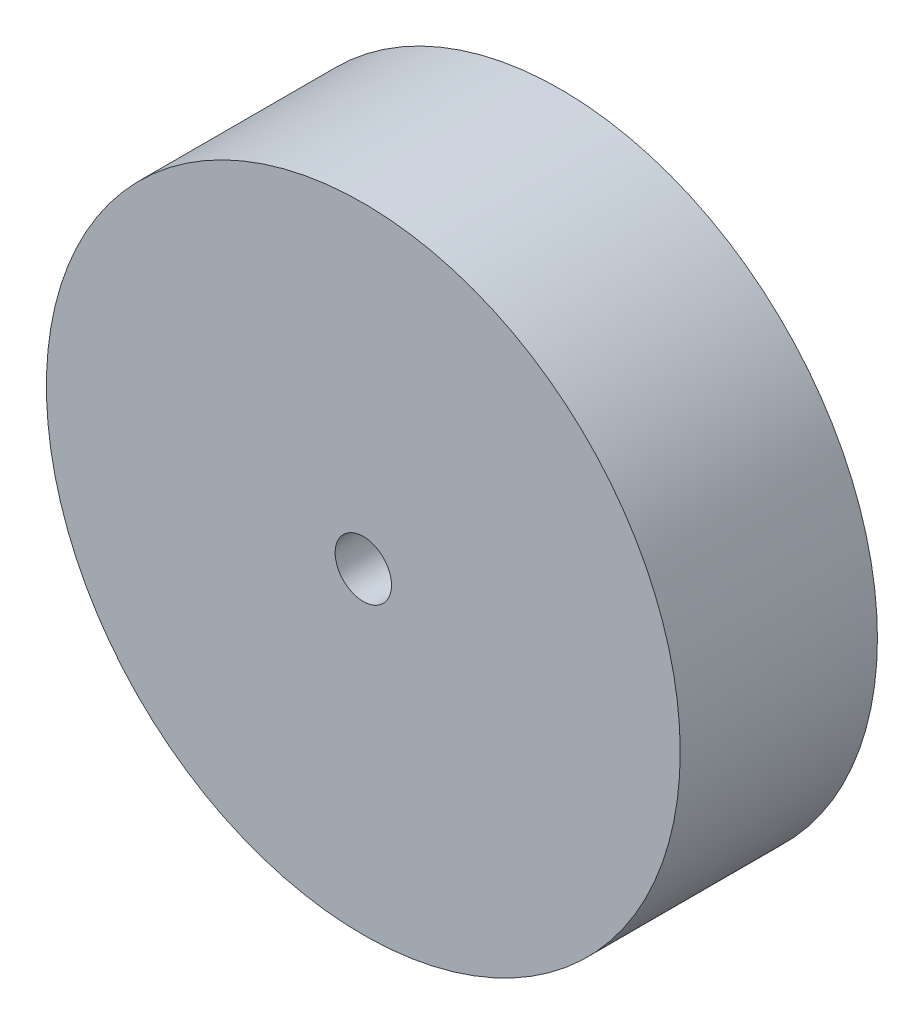
SolidWorks part; units mm, degrees
material "Beech"
ref_plane "Front Plane" through (0, 0, 0) normal (0, 0, 1) x (1, 0, 0)
ref_plane "Top Plane" through (0, 0, 0) normal (0, 1, 0) x (1, 0, 0)
ref_plane "Right Plane" through (0, 0, 0) normal (1, 0, 0) x (0, 0, -1)
sketch "Sketch1" plane through (0, 0, 0) normal (0, 0, 1) x (1, 0, 0)
  circle A0 centre (0, 0) radius 0.254
  circle A1 centre (0, 0) radius 2.8575
  dimension "D1" = 0.508
  dimension "D2" = 5.715
extrude "Boss-Extrude1" add sketch "Sketch1" along normal blind 1.778
